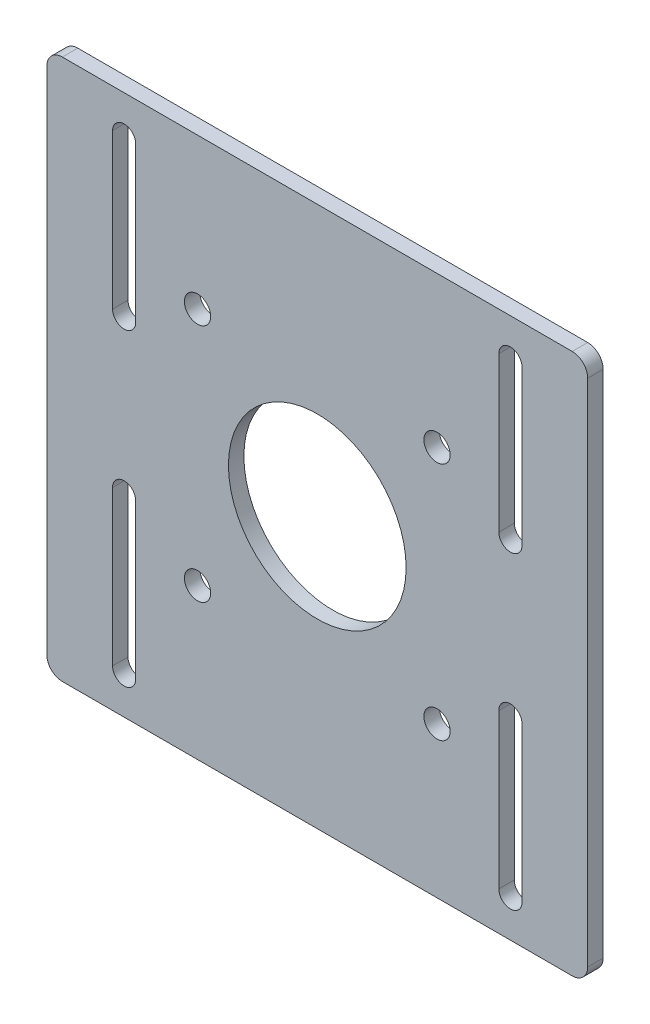
SolidWorks part; units mm, degrees
ref_plane "Vorne" through (0, 0, 0) normal (0, 0, 1) x (1, 0, 0)
ref_plane "Oben" through (0, 0, 0) normal (0, 1, 0) x (1, 0, 0)
ref_plane "Rechts" through (0, 0, 0) normal (1, 0, 0) x (0, 0, -1)
ref_plane "E_Boden" through (0, 1, 0) normal (0, 1, 0) x (1, 0, 0)
sketch "Skizze1" plane through (0, 0, 0) normal (0, 0, 1) x (1, 0, 0)
  line L0 (0, 8.4271) -> (0, -17.0097) construction
  line L1 (-16.4189, 0) -> (17.6005, 0) construction
  line L3 (-35, 35) -> (35, 35)
  line L4 (-35, 35) -> (-35, -35)
  line L5 (-35, -35) -> (35, -35)
  line L6 (35, 35) -> (35, -35)
  dimension "D1" = 70
  dimension "D2" = 70
extrude "Aufsatz-Linear austragen1" add sketch "Skizze1" along normal blind 2
fillet "Verrundung2" radius 2 4 edges at (-35, 35, 1) (-35, -35, 1) (35, -35, 1) (35, 35, 1)
hole_wizard "Ø23.0 (23) Durchmesser Bohrung1" positions "Skizze2" profile "Skizze3" hole size "Ø23.0" standard "DIN" end condition through all
sketch "Skizze2" plane through (0, 0, 2) normal (0, 0, 1) x (1, 0, 0)
  point P0 (0, 0)
sketch "Skizze3" plane through (0, 0, 2) normal (1, 0, 0) x (0, -1, 0)
  line L0 (0, 0) -> (0, 2)
  line L1 (0, 2) -> (11.5, 2)
  line L2 (11.5, 2) -> (11.5, 0)
  line L5 (11.5, 0) -> (0, 0)
  line L11 (0, -6.35) -> (0, 107.95) construction
  dimension "Bohrerdurchmesser" = 23
  dimension "Bohrungstiefe" = 2
hole_wizard "Durchgangsloch für M31" positions "Skizze4" profile "Skizze5" hole size "M3" standard "DIN" end condition through all
sketch "Skizze4" plane through (0, 0, 2) normal (0, 0, 1) x (1, 0, 0)
  line L0 (0, 35) -> (0, -35) construction
  line L1 (33, 35) -> (-33, 35) construction
  line L2 (-33, -35) -> (33, -35) construction
  line L4 (67.0133, -10.5588) -> (66.8256, -10.2773) construction
  line L6 (-35, 0) -> (35, 0) construction
  line L7 (-35, 33) -> (-35, -33) construction
  line L8 (35, -33) -> (35, 33) construction
  point P0 (-15.5, 15.5)
  point P2 (15.5, 15.5)
  point P4 (15.5, -15.5)
  point P6 (-15.5, -15.5)
  dimension "D1" = 31
  dimension "D2" = 31
  dimension "D3" = 31
sketch "Skizze5" plane through (-15.5, 15.5, 2) normal (1, 0, 0) x (0, -1, 0)
  line L0 (0, 0) -> (0, 2)
  line L1 (0, 2) -> (1.7, 2)
  line L2 (1.7, 2) -> (1.7, 0)
  line L5 (1.7, 0) -> (0, 0)
  line L11 (0, -6.35) -> (0, 107.95) construction
  dimension "Bohrerdurchmesser" = 3.4
  dimension "Bohrungstiefe" = 2
sketch "Skizze8" plane through (0, 0, 2) normal (0, 0, 1) x (1, 0, 0)
  line L0 (-25, 35) -> (-25, 5) construction
  line L1 (33, 35) -> (-33, 35) construction
  line L2 (0, 35) -> (0, -35) construction
  line L3 (25, 35) -> (25, 12.639) construction
  line L4 (-25, -35) -> (-25, -5) construction
  line L5 (-33, -35) -> (33, -35) construction
  line L6 (25, -35) -> (25, -5) construction
  line L7 (-35, 0) -> (35, 0) construction
  line L8 (-35, 33) -> (-35, -33) construction
  line L9 (35, -33) -> (35, 33) construction
  line L10 (-26.5, 30) -> (-26.5, 10)
  line L11 (-23.5, 30) -> (-23.5, 10)
  line L18 (-25, 20) -> (-35.9791, 20) construction
  line L19 (-35.9791, 20) -> (-16.4669, 20) construction
  line L20 (-25, -12.603) -> (-25, -37.6924) construction
  line L21 (-26.5, -10) -> (-26.5, -30)
  line L22 (-23.5, -10) -> (-23.5, -30)
  line L23 (-25, -25.1477) -> (-36.3551, -25.1477) construction
  line L24 (25, -12.1814) -> (25, -37.6275) construction
  line L25 (23.5, -10) -> (23.5, -30)
  line L26 (26.5, -10) -> (26.5, -30)
  line L28 (25, 28.8483) -> (25, 6.6195) construction
  line L29 (23.5, 30) -> (23.5, 10)
  line L30 (26.5, 30) -> (26.5, 10)
  arc A0 (-23.5, 30) -> (-26.5, 30) centre (-25, 30) ccw
  arc A1 (-23.5, 10) -> (-26.5, 10) centre (-25, 10) cw
  arc A8 (-23.5, -10) -> (-26.5, -10) centre (-25, -10) ccw
  arc A9 (-23.5, -30) -> (-26.5, -30) centre (-25, -30) cw
  arc A10 (26.5, -10) -> (23.5, -10) centre (25, -10) ccw
  arc A11 (26.5, -30) -> (23.5, -30) centre (25, -30) cw
  arc A12 (26.5, 30) -> (23.5, 30) centre (25, 30) ccw
  arc A13 (26.5, 10) -> (23.5, 10) centre (25, 10) cw
  point P12 (-25, 20)
  point P13 (25, 20)
  point P14 (25, -20)
  point P15 (-25, -20)
  point P32 (-25, -25.1477)
  point P43 (25, -24.9045)
  point P49 (0, 0)
  point P54 (29.5, 30.2339)
  point P58 (25, 17.7339)
  point P67 (-29.5, -12.9484)
  point P68 (29.5, -12.4045)
  dimension "D5" = 1.5
  dimension "D8" = 1.5
  dimension "D11" = 1.5
  dimension "D14" = 1.5
  dimension "D1" = 40
  dimension "D2" = 40
  dimension "D3" = 50
  dimension "D4" = 20
  dimension "D6" = 10
  dimension "D7" = 20
  dimension "D9" = 10
  dimension "D10" = 20
  dimension "D12" = 10
  dimension "D13" = 20
  dimension "D15" = 10
extrude "Schnitt-Linear austragen1" cut sketch "Skizze8" against normal through all contours A1 L10 A0 L11 | L29 A13 L30 A12 | L21 A9 L22 A8 | L25 A11 L26 A10
